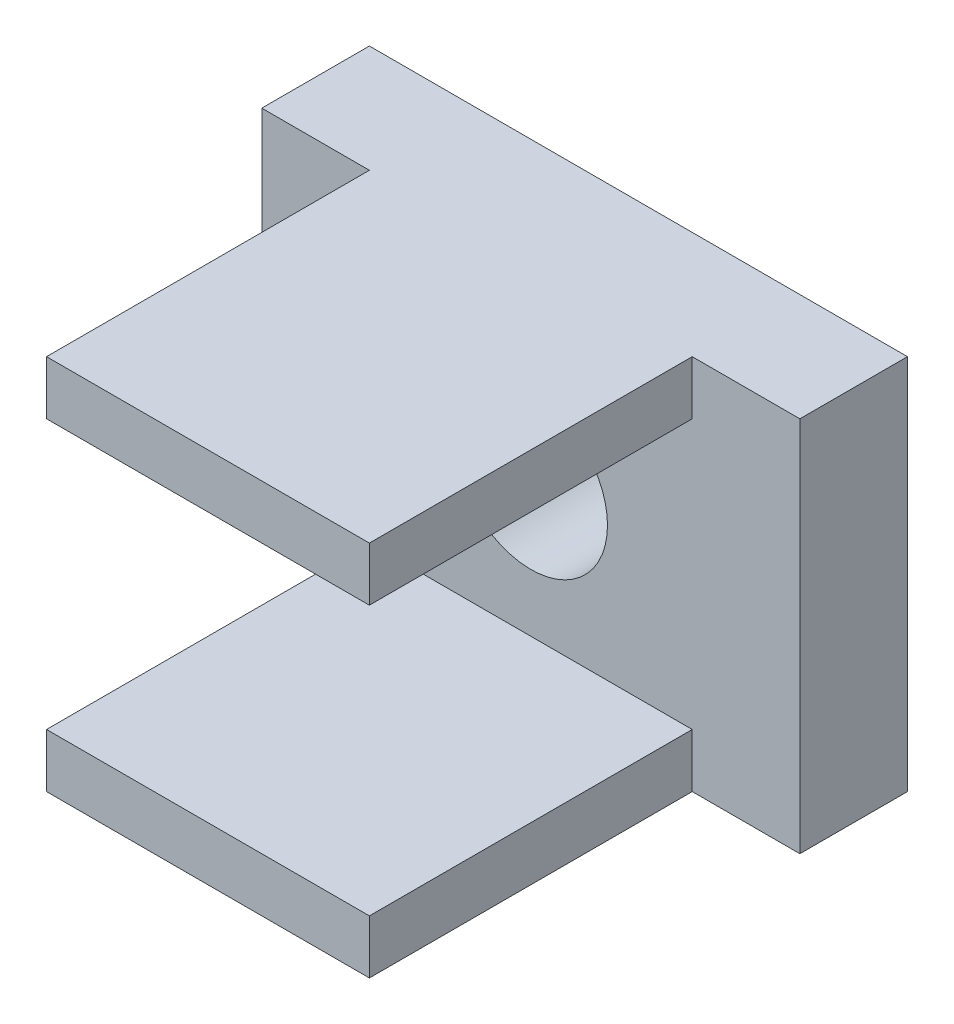
SolidWorks part; units mm, degrees
ref_plane "Front Plane" through (0, 0, 0) normal (0, 0, 1) x (1, 0, 0)
ref_plane "Top Plane" through (0, 0, 0) normal (0, 1, 0) x (1, 0, 0)
ref_plane "Right Plane" through (0, 0, 0) normal (1, 0, 0) x (0, 0, -1)
sketch "Sketch1" plane through (0, 0, 0) normal (0, 0, 1) x (1, 0, 0)
  line L1 (-5, 3.5) -> (5, 3.5)
  line L2 (-5, 3.5) -> (-5, -3.5)
  line L3 (-5, -3.5) -> (5, -3.5)
  line L4 (5, 3.5) -> (5, -3.5)
  line L5 (-5, 3.5) -> (5, -3.5) construction
  line L6 (-5, -3.5) -> (5, 3.5) construction
  point P0 (0, 0)
  dimension "D1" = 7
  dimension "D2" = 10
extrude "Boss-Extrude1" add sketch "Sketch1" along normal blind 2
sketch "Sketch2" plane through (0, 0, 2) normal (0, 0, 1) x (1, 0, 0)
  line L0 (0, 6.4261) -> (0, -6.3886) construction
  line L1 (-5.6215, 0) -> (6.293, 0) construction
  line L2 (5, 3.5) -> (-5, 3.5) construction
  line L3 (-3, 3.5) -> (3, 3.5)
  line L4 (-3, 3.5) -> (-3, 2.5)
  line L5 (-3, 2.5) -> (3, 2.5)
  line L6 (3, 3.5) -> (3, 2.5)
  line L7 (-3, -2.5) -> (3, -2.5)
  line L8 (3, -3.5) -> (3, -2.5)
  line L9 (-3, -3.5) -> (3, -3.5)
  line L10 (-3, -3.5) -> (-3, -2.5)
  dimension "D1" = 1
  dimension "D2" = 6
extrude "Boss-Extrude2" add sketch "Sketch2" along normal blind 6
sketch "Sketch3" plane through (0, 0, 2) normal (0, 0, 1) x (1, 0, 0)
  circle A0 centre (0, 0) radius 1.425
  dimension "D1" = 2.85
extrude "Cut-Extrude1" cut sketch "Sketch3" against normal through all
